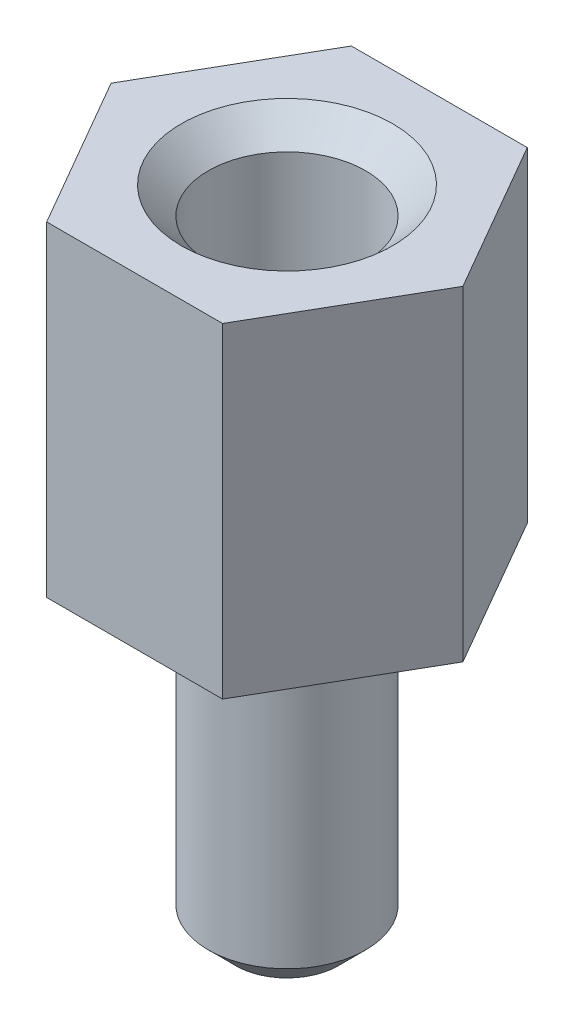
SolidWorks part; units mm, degrees
ref_plane "Front Plane" through (0, 0, 0) normal (0, 0, 1) x (1, 0, 0)
ref_plane "Top Plane" through (0, 0, 0) normal (0, 1, 0) x (1, 0, 0)
ref_plane "Right Plane" through (0, 0, 0) normal (1, 0, 0) x (0, 0, -1)
ref_plane "Plane1" through (0, 6, 0) normal (0, 1, 0) x (1, 0, 0)
sketch "Sketch1" plane through (0, 6, 0) normal (0, 1, 0) x (1, 0, 0)
  line L0 (1.6224, -2.81) -> (3.2447, 0)
  line L1 (3.2447, 0) -> (1.6224, 2.81)
  line L2 (1.6224, 2.81) -> (-1.6224, 2.81)
  line L3 (-1.6224, 2.81) -> (-3.2447, 0)
  line L4 (-3.2447, 0) -> (-1.6224, -2.81)
  line L5 (-1.6224, -2.81) -> (1.6224, -2.81)
extrude "Boss-Extrude1" add sketch "Sketch1" against normal blind 6
ref_plane "Plane2" through (0, 0, 0) normal (0, 0, -1) x (-1, 0, 0)
sketch "Sketch2" plane through (0, 0, 0) normal (0, 0, -1) x (-1, 0, 0)
  line L0 (-1.45, -6) -> (0, -6)
  line L1 (0, -6) -> (0, 0)
  line L2 (0, 0) -> (-1.45, 0)
  line L3 (-1.45, 0) -> (-1.45, -6)
  line L4 (0, -6) -> (0, 0) construction
revolve "Revolve1" add sketch "Sketch2" angle 360 about L4
hole_wizard "Ø2.9 (2.9) Diameter Hole1" positions "Sketch4" profile "Sketch3" hole size "Ø2.9" standard "ANSI Metric"
sketch "Sketch4" plane through (0, 6, 0) normal (0, 1, 0) x (1, 0, 0)
  point P0 (0, 0)
sketch "Sketch3" plane through (0, 6, 0) normal (1, 0, 0) x (0, 0, 1)
  line L0 (0, 0) -> (0, 5)
  line L1 (0, 5) -> (1.45, 5)
  line L2 (1.45, 5) -> (1.45, 0)
  line L5 (1.45, 0) -> (0, 0)
  line L10 (0, 5) -> (-1.45, 5) construction
  line L11 (0, -6.35) -> (0, 107.95) construction
  dimension "Hole Dia." = 2.9
  dimension "Hole Depth" = 5
  dimension "Drill Angle" = 180
chamfer "Chamfer1" distance 0.5 angle 45 2 edges at (0, -6, 1.45) (0, 6, 1.45)
